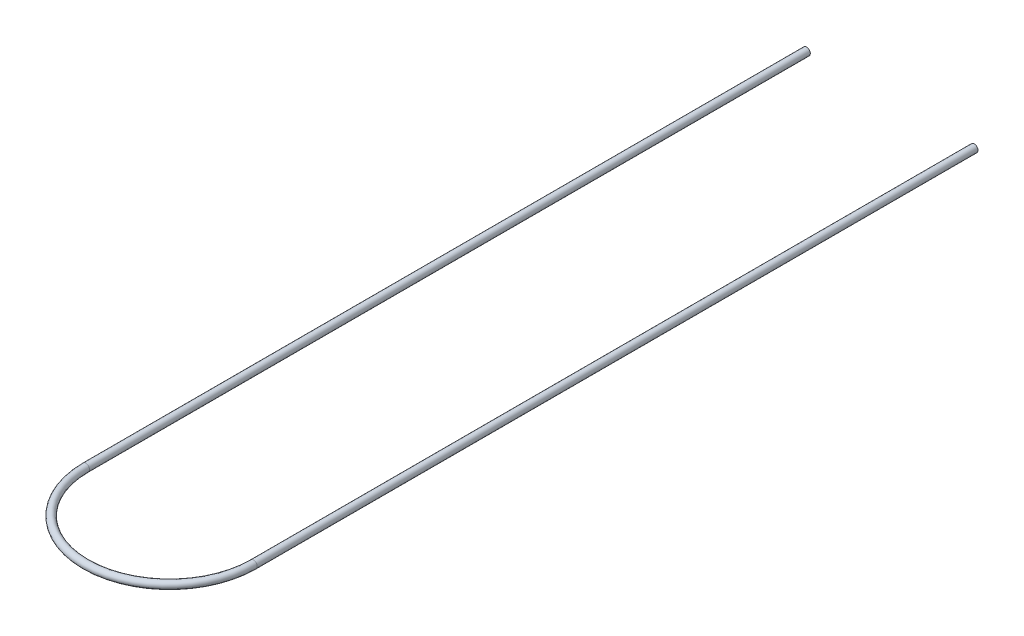
SolidWorks part; units mm, degrees
ref_plane "Front Plane" through (0, 0, 0) normal (0, 0, 1) x (1, 0, 0)
ref_plane "Top Plane" through (0, 0, 0) normal (0, 1, 0) x (1, 0, 0)
ref_plane "Right Plane" through (0, 0, 0) normal (1, 0, 0) x (0, 0, -1)
sketch "Sketch1" plane through (0, 0, 0) normal (0, 1, 0) x (1, 0, 0)
  line L0 (457.85, -300) -> (457.85, -2440)
  line L2 (-40, -300) -> (-40, -2440)
  arc A0 (-40, -2440) -> (457.85, -2440) centre (208.925, -2440) ccw
  dimension "D1" = 2140
  dimension "D2" = 497.85
ref_plane "Plane1" through (457.85, 0, 300) normal (0, 0, -1) x (-1, 0, 0)
sketch "Sketch2" plane through (457.85, 0, 300) normal (0, 0, -1) x (-1, 0, 0)
  circle A0 centre (0, 0) radius 9.95
  circle A1 centre (0, 0) radius 11.1
  dimension "D1" = 22.2
  dimension "D2" = 19.9
sweep "Sweep1" add profiles "Sketch2" path "Sketch1"
